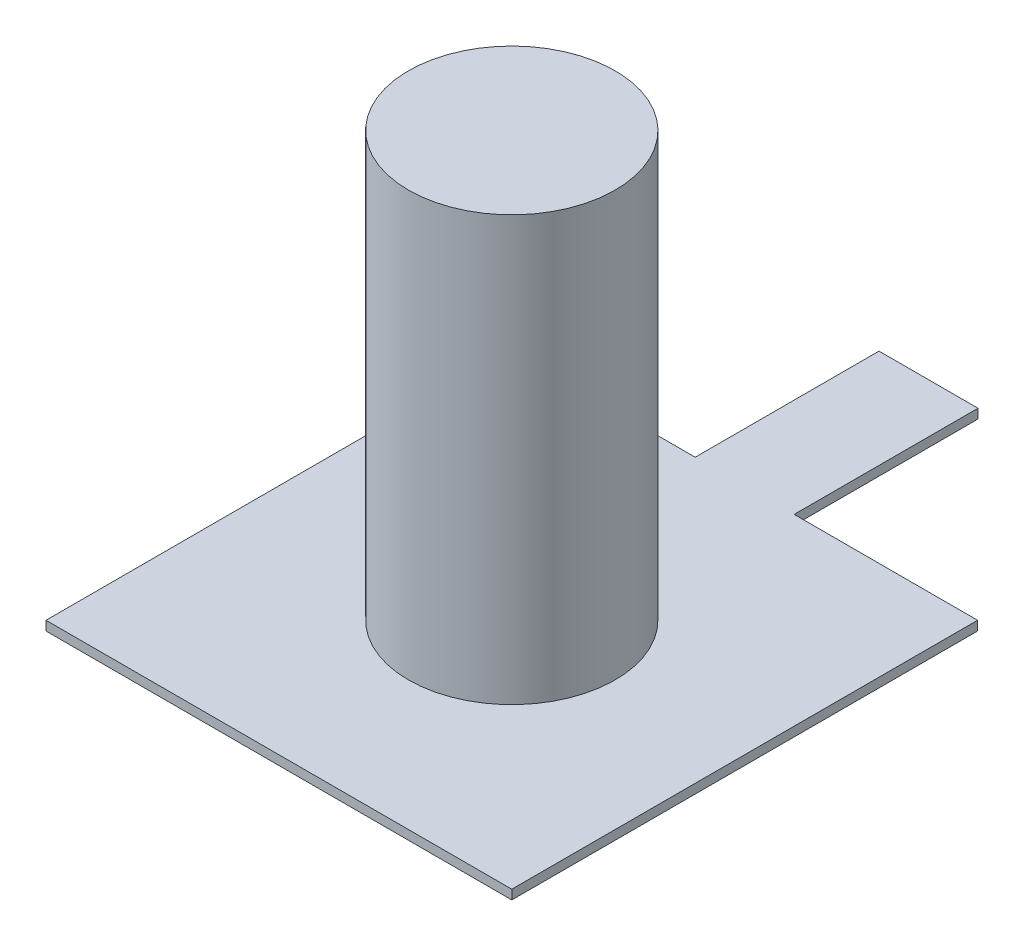
SolidWorks part; units mm, degrees
ref_plane "Front Plane" through (0, 0, 0) normal (0, 0, 1) x (1, 0, 0)
ref_plane "Top Plane" through (0, 0, 0) normal (0, 1, 0) x (1, 0, 0)
ref_plane "Right Plane" through (0, 0, 0) normal (1, 0, 0) x (0, 0, -1)
sketch "Sketch1" plane through (0, 0, 0) normal (0, 1, 0) x (1, 0, 0)
  line L0 (0, 0) -> (16.47, 0)
  line L2 (16.47, 0) -> (16.47, 16.47)
  line L3 (6.485, 16.47) -> (6.485, 22.97)
  line L4 (0, 0) -> (0, 16.47)
  line L5 (6.485, 22.97) -> (9.985, 22.97)
  line L6 (9.985, 22.97) -> (9.985, 16.47)
  line L7 (6.485, 16.47) -> (0, 16.47)
  line L8 (9.985, 16.47) -> (16.47, 16.47)
  dimension "D1" = 3.5
  dimension "D2" = 16.47
  dimension "D3" = 6.5
extrude "Boss-Extrude1" add sketch "Sketch1" along normal blind 0.33
sketch "Sketch2" plane through (0, 0.33, 0) normal (0, 1, 0) x (1, 0, 0)
  line L1 (0, 8.235) -> (16.47, 8.235) construction
  line L2 (0, 16.47) -> (0, 0) construction
  line L3 (16.47, 0) -> (16.47, 16.47) construction
  circle A0 centre (8.235, 8.235) radius 3.655
  point P8 (0, 0)
  point P9 (8.235, 8.235)
  dimension "D1" = 7.31
extrude "Boss-Extrude2" add sketch "Sketch2" along normal blind 15
